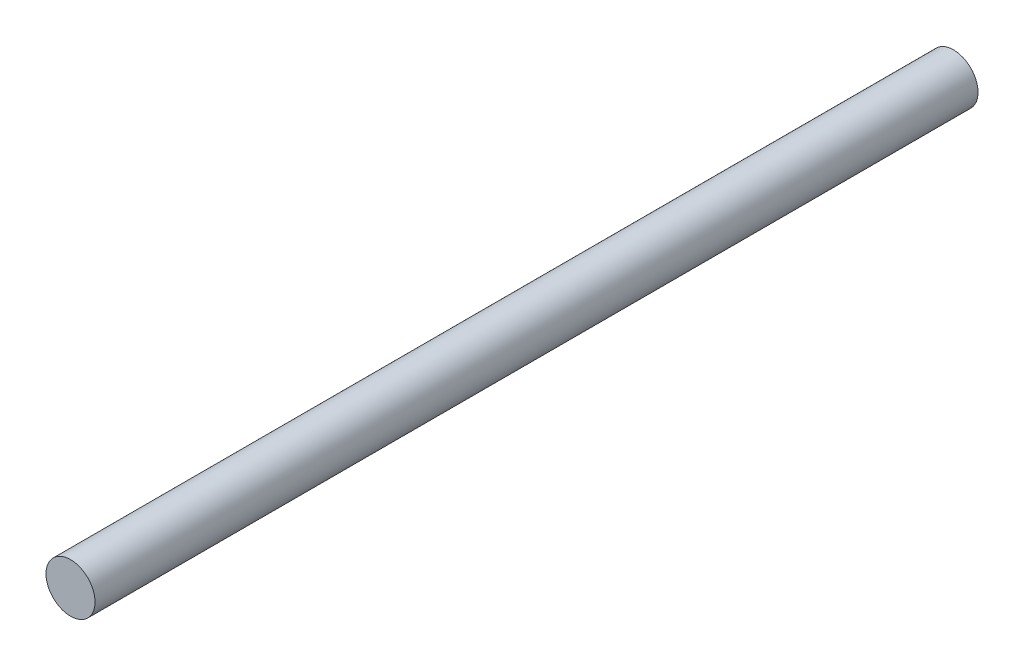
SolidWorks part; units mm, degrees
ref_plane "Front Plane" through (0, 0, 0) normal (0, 0, 1) x (1, 0, 0)
ref_plane "Top Plane" through (0, 0, 0) normal (0, 1, 0) x (1, 0, 0)
ref_plane "Right Plane" through (0, 0, 0) normal (1, 0, 0) x (0, 0, -1)
sketch "Sketch1" plane through (0, 0, 0) normal (0, 0, 1) x (1, 0, 0)
  circle A0 centre (0, 0) radius 5
  dimension "D1" = 10
extrude "Boss-Extrude1" add sketch "Sketch1" along normal blind 180
